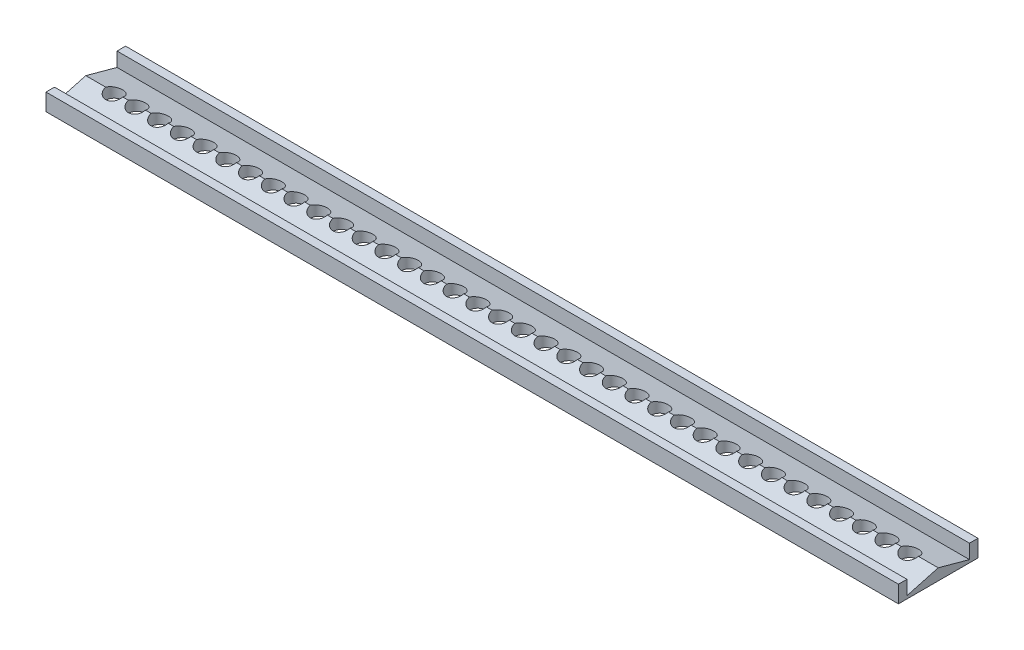
SolidWorks part; units mm, degrees
ref_plane "前视基准面" through (0, 0, 0) normal (0, 0, 1) x (1, 0, 0)
ref_plane "上视基准面" through (0, 0, 0) normal (0, 1, 0) x (1, 0, 0)
ref_plane "右视基准面" through (0, 0, 0) normal (1, 0, 0) x (0, 0, -1)
sketch "Sketch2" plane through (0, 0, 0) normal (1, 0, 0) x (0, 0, -1)
  line L0 (-5.5, 1.5) -> (5.5, 1.5) construction
  line L1 (-7, -1.5) -> (7, -1.5)
  line L2 (-7, -1.5) -> (-7, 1.5)
  line L3 (-7, 1.5) -> (7, 1.5) construction
  line L4 (7, -1.5) -> (7, 1.5)
  line L5 (-7, -1.5) -> (7, 1.5) construction
  line L6 (-7, 1.5) -> (7, -1.5) construction
  line L7 (-7, 1.5) -> (-5.5, 1.5)
  line L8 (-5.5, 1.5) -> (-5.5, -1)
  line L9 (-5.5, -1) -> (5.5, -1) construction
  line L10 (5.5, -1) -> (5.5, 1.5)
  line L11 (5.5, 1.5) -> (7, 1.5)
  line L12 (0, -1) -> (0, 0.5) construction
  line L13 (-5.5, -1) -> (0, 0.5)
  line L14 (0, 0.5) -> (5.5, -1)
  point P0 (0, 0)
  point P5 (0, 1.5)
  dimension "D1" = 1.5
  dimension "D2" = 0.5
  dimension "D3" = 14
  dimension "D4" = 3
  dimension "D5" = 1.5
extrude "Boss-Extrude1" add sketch "Sketch2" along normal blind 150
sketch "Sketch3" plane through (0, -1.5, 0) normal (0, -1, 0) x (1, 0, 0)
  line L0 (0, 0) -> (5, 0) construction
  circle A0 centre (5, 0) radius 1.5
extrude "Cut-Extrude1" cut sketch "Sketch3" against normal blind 5
pattern_linear "LPattern1" count 36 spacing 4 along (1, 0, 0) of "Cut-Extrude1"
